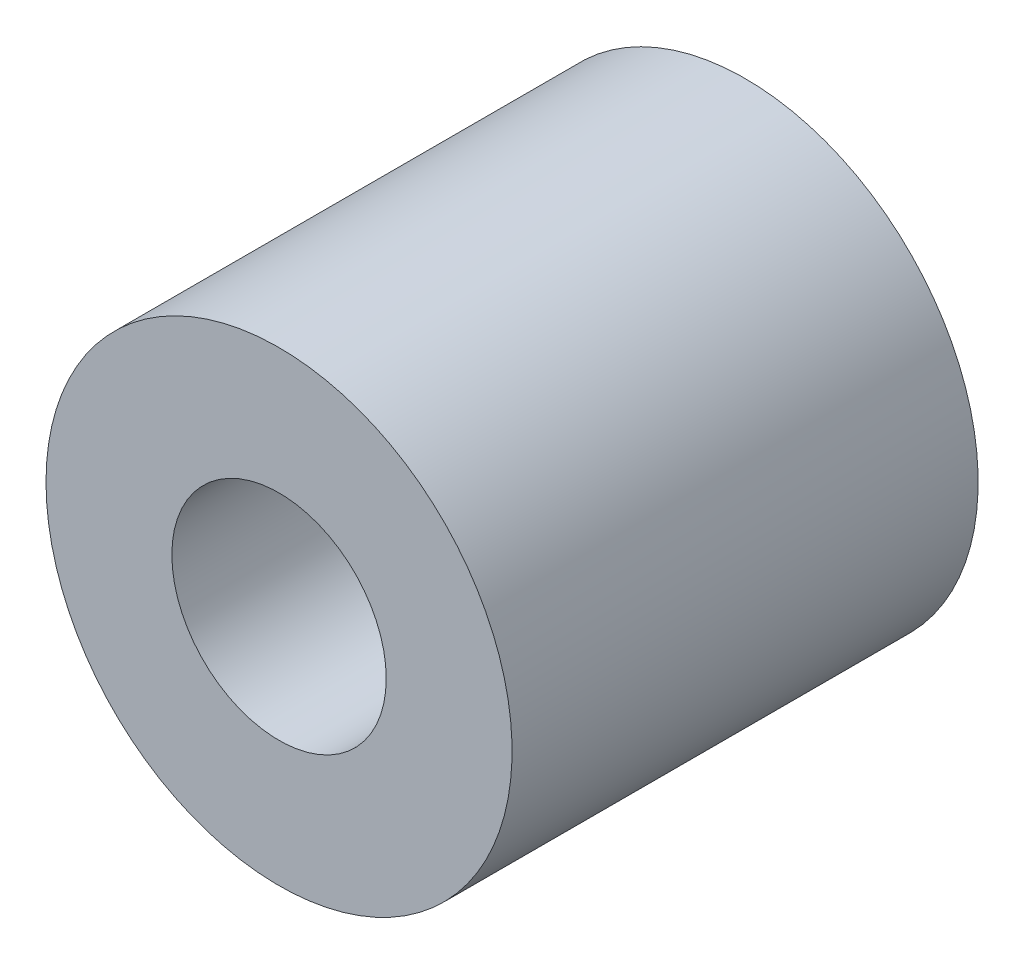
SolidWorks part; units mm, degrees
ref_plane "Front Plane" through (0, 0, 0) normal (0, 0, 1) x (1, 0, 0)
ref_plane "Top Plane" through (0, 0, 0) normal (0, 1, 0) x (1, 0, 0)
ref_plane "Right Plane" through (0, 0, 0) normal (1, 0, 0) x (0, 0, -1)
sketch "Sketch1" plane through (0, 0, 0) normal (0, 0, 1) x (1, 0, 0)
  line L0 (0, 1.4605) -> (0, 3.175) construction
  line L1 (0, -1.4605) -> (0, -3.175) construction
  circle A0 centre (0, 0) radius 3.175
  circle A1 centre (0, 0) radius 1.4605
  dimension "OD" = 6.35
  dimension "ID" = 2.921
sketch "Sketch2" plane through (0, 0, 0) normal (1, 0, 0) x (0, 0, -1)
  line L0 (-3.175, 1.4605) -> (3.175, 1.4605) construction
  line L1 (-3.175, -1.4605) -> (3.175, -1.4605) construction
  line L2 (-3.175, -3.175) -> (3.175, -3.175) construction
  line L3 (-3.175, 3.175) -> (3.175, 3.175) construction
  dimension "Length" = 6.35
extrude "Extrude1" add sketch "Sketch1" along normal up to vertex (3.175 mm away) and the other way up to vertex (3.175 mm away) up to point (0, 1.4605, 3.175) other way up to point (0, 1.4605, -3.175)
sketch "Sketch3" plane through (0, 0, 3.175) normal (0, 0, 1) x (1, 0, 0)
  circle A0 centre (0, 0) radius 1.4605 construction
  circle A3 centre (0, 0) radius 1.4605
  point P3 (-1.4605, 0)
